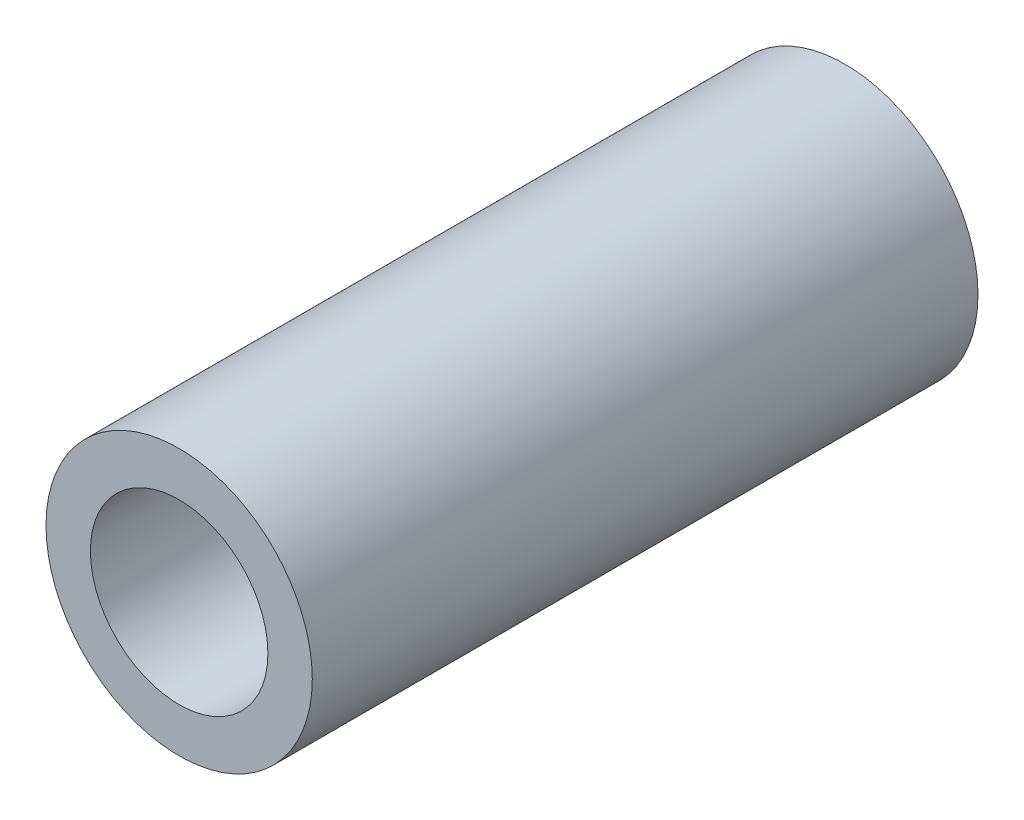
SolidWorks part; units mm, degrees
ref_plane "Front Plane" through (0, 0, 0) normal (0, 0, 1) x (1, 0, 0)
ref_plane "Top Plane" through (0, 0, 0) normal (0, 1, 0) x (1, 0, 0)
ref_plane "Right Plane" through (0, 0, 0) normal (1, 0, 0) x (0, 0, -1)
sketch "Sketch1" plane through (0, 0, 0) normal (0, 0, 1) x (1, 0, 0)
  circle A0 centre (0, 0) radius 2
  circle A1 centre (0, 0) radius 3
  dimension "D1" = 4
  dimension "D2" = 6
extrude "Boss-Extrude1" add sketch "Sketch1" along normal blind 15
